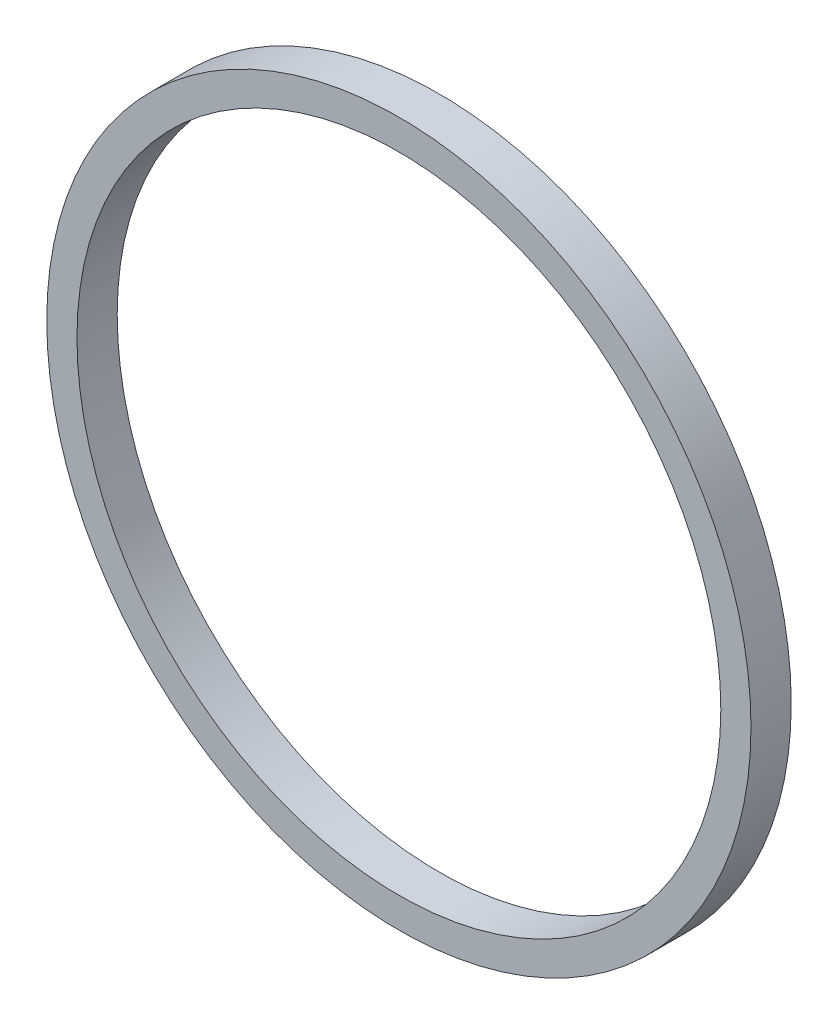
SolidWorks part; units mm, degrees
ref_plane "Front Plane" through (0, 0, 0) normal (0, 0, 1) x (1, 0, 0)
ref_plane "Top Plane" through (0, 0, 0) normal (0, 1, 0) x (1, 0, 0)
ref_plane "Right Plane" through (0, 0, 0) normal (1, 0, 0) x (0, 0, -1)
sketch "Sketch1" plane through (0, 0, 0) normal (0, 0, 1) x (1, 0, 0)
  circle A0 centre (0, 0) radius 17.5
  circle A1 centre (0, 0) radius 16
  dimension "D1" = 32
  dimension "D2" = 35
extrude "Boss-Extrude1" add sketch "Sketch1" along normal blind 2
